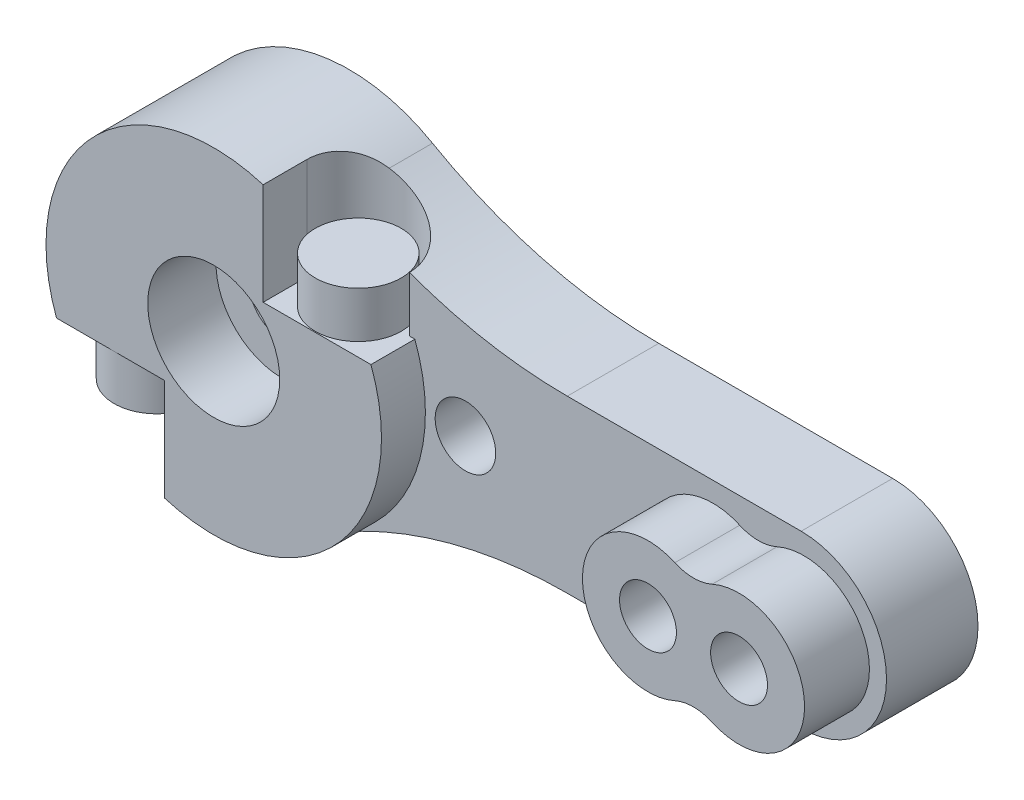
SolidWorks part; units mm, degrees
ref_plane "Piano frontale" through (0, 0, 0) normal (0, 0, 1) x (1, 0, 0)
ref_plane "Piano superiore" through (0, 0, 0) normal (0, 1, 0) x (1, 0, 0)
ref_plane "Piano destro" through (0, 0, 0) normal (1, 0, 0) x (0, 0, -1)
sketch "Schizzo1" plane through (0, 0, 0) normal (0, 0, 1) x (1, 0, 0)
  line L1 (13.6035, -3.75) -> (23.88, -3.75)
  line L3 (13.6035, 3.75) -> (23.88, 3.75)
  line L5 (18.7417, -3.75) -> (23.88, 3.75) construction
  line L6 (18.7417, 3.75) -> (23.88, -3.75) construction
  circle A0 centre (0, 0) radius 1.45
  arc A1 (3.663, 6.3952) -> (3.663, -6.3952) centre (0, 0) ccw
  arc A2 (23.88, 3.75) -> (23.88, -3.75) centre (23.88, 0) cw
  circle A3 centre (9.13, 0) radius 1.33
  arc A4 (3.663, -6.3952) -> (13.6035, -3.75) centre (13.6035, -23.75) cw
  arc A5 (3.663, 6.3952) -> (13.6035, 3.75) centre (13.6035, 23.75) ccw
  point P4 (21.3109, 0)
  point P9 (27.63, 0)
  point P11 (-7.37, 0)
  dimension "D1" = 2.9
  dimension "D2" = 14.74
  dimension "D5" = 2.66
  dimension "D7" = 20
  dimension "D3" = 7.5
  dimension "D4" = 35
  dimension "D6" = 16.5
extrude "Estrusione-Estrusione1" add sketch "Schizzo1" along normal blind 4.02
sketch "Schizzo2" plane through (0, 0, 4.02) normal (0, 0, 1) x (1, 0, 0)
  circle A0 centre (0, 0) radius 7.37
  arc A1 (3.663, 6.3952) -> (3.663, -6.3952) centre (0, 0) ccw construction
  circle A3 centre (0, 0) radius 1.45
  circle A4 centre (0, 0) radius 1.45
  dimension "D1" = 0
extrude "Estrusione-Estrusione2" add sketch "Schizzo2" along normal blind 5.95 from surface at -4.02 starting at face at (1.45, 0, 0)
sketch "Schizzo3" plane through (0, 0, 4.02) normal (0, 0, 1) x (1, 0, 0)
  line L0 (24, 0) -> (0, 0) construction
  arc A0 (22.8197, -2.627) -> (22.8197, 2.627) centre (24, 0) ccw
  arc A1 (21.1803, 2.627) -> (21.1803, -2.627) centre (20, 0) ccw
  arc A2 (22.8197, -2.627) -> (21.1803, -2.627) centre (22, -4.4513) ccw
  arc A3 (21.1803, 2.627) -> (22.8197, 2.627) centre (22, 4.4513) ccw
  dimension "D2" = 5.76
  dimension "D4" = 2
  dimension "D1" = 4
  dimension "D3" = 24
extrude "Estrusione-Estrusione3" add sketch "Schizzo3" along normal blind 6.87 from surface at -4.02 starting at face at (12.444, 0, 0)
hole_wizard "Foro filettato M3x0.5-1" positions "Schizzo5" profile "Schizzo4" tap size "M3x0.5" standard "Ansi Metric" end condition through all
sketch "Schizzo5" plane through (0, 0, 6.87) normal (0, 0, 1) x (1, 0, 0)
  point P0 (24, 0)
  point P3 (20, 0)
sketch "Schizzo4" plane through (24, 0, 6.87) normal (1, 0, 0) x (0, -1, 0)
  line L0 (0, 0) -> (0, 6.87)
  line L1 (0, 6.87) -> (1.25, 6.87)
  line L2 (1.25, 6.87) -> (1.25, 0)
  line L5 (1.25, 0) -> (0, 0)
  line L11 (0, -6.35) -> (0, 107.95) construction
  dimension "Thru Tap Drill Dia." = 2.5
  dimension "Thru Tap Drill Depth" = 6.87
cosmetic thread "Filettatura del foro1" parameters "D2"=3
cosmetic thread "Filettatura del foro2" parameters "D2"=3
sketch "Schizzo6" plane through (0, 0, 0) normal (0, 0, -1) x (-1, 0, 0)
  circle A0 centre (0, 0) radius 4
  dimension "D1" = 8
extrude "Taglio-Estrusione1" cut sketch "Schizzo6" against normal blind 1.07
sketch "Schizzo8" plane through (0, 0, 5.95) normal (0, 0, 1) x (1, 0, 0)
  circle A0 centre (0, 0) radius 2.9
  dimension "D1" = 5.8
extrude "Taglio-Estrusione2" cut sketch "Schizzo8" against normal blind 3
ref_plane "Piano1" through (0, 7.37, 0) normal (0, 1, 0) x (1, 0, 0)
sketch "Schizzo9" plane through (0, 7.37, 0) normal (0, 1, 0) x (1, 0, 0)
  line L0 (6.67, -5.95) -> (6.67, -4.02)
  line L1 (-7.37, -5.95) -> (7.37, -5.95) construction
  line L2 (3.663, -4.02) -> (13.6035, -4.02) construction
  line L3 (2.17, -5.95) -> (2.17, -4.02)
  line L4 (2.17, -5.95) -> (6.67, -5.95)
  line L5 (7.37, -5.95) -> (7.37, -4.02) construction
  line L7 (6.67, -4.02) -> (7.37, -4.02)
  line L8 (6.67, -4.02) -> (6.67, -5.95)
  line L9 (6.67, -5.95) -> (7.37, -5.95)
  line L10 (7.37, -4.02) -> (7.37, -5.95)
  arc A0 (2.17, -4.02) -> (6.67, -4.02) centre (4.42, -4.02) cw
  dimension "D1" = 4.5
  dimension "D2" = 0.7
extrude "Taglio-Estrusione3" cut sketch "Schizzo9" against normal blind 4.8 contours A0 L3 L4 L0 | L10 L7 L0 L9
ref_plane "Piano2" through (0, -7.37, 0) normal (0, -1, 0) x (-1, 0, 0)
sketch "Schizzo11" plane through (0, -7.37, 0) normal (0, -1, 0) x (-1, 0, 0)
  line L0 (6.67, -5.95) -> (6.67, -4.02)
  line L1 (2.17, -5.95) -> (2.17, -4.02)
  line L2 (2.17, -5.95) -> (6.67, -5.95)
  line L3 (6.67, -4.02) -> (7.37, -4.02)
  line L4 (6.67, -4.02) -> (6.67, -5.95)
  line L5 (6.67, -5.95) -> (7.37, -5.95)
  line L6 (7.37, -4.02) -> (7.37, -5.95)
  line L7 (7.37, -5.95) -> (7.37, 0) construction
  line L8 (-7.37, -5.95) -> (7.37, -5.95) construction
  line L9 (-13.6035, -4.02) -> (-3.663, -4.02) construction
  arc A0 (2.17, -4.02) -> (6.67, -4.02) centre (4.42, -4.02) cw
  dimension "D1" = 4.5
  dimension "D2" = 0.7
extrude "Taglio-Estrusione4" cut sketch "Schizzo11" against normal blind 4.8 contours A0 L1 L2 L0 | L6 L3 L0 L5
sketch "Schizzo12" plane through (0, 2.57, 0) normal (0, 1, 0) x (1, 0, 0)
  circle A0 centre (4.42, -4.02) radius 1.89
  dimension "D1" = 3.78
extrude "Estrusione-Estrusione4" add sketch "Schizzo12" along normal blind 2.03
sketch "Schizzo13" plane through (0, -2.57, 0) normal (0, -1, 0) x (-1, 0, 0)
  circle A0 centre (4.42, -4.02) radius 1.89
  dimension "D1" = 3.78
extrude "Estrusione-Estrusione5" add sketch "Schizzo13" along normal blind 2.03
